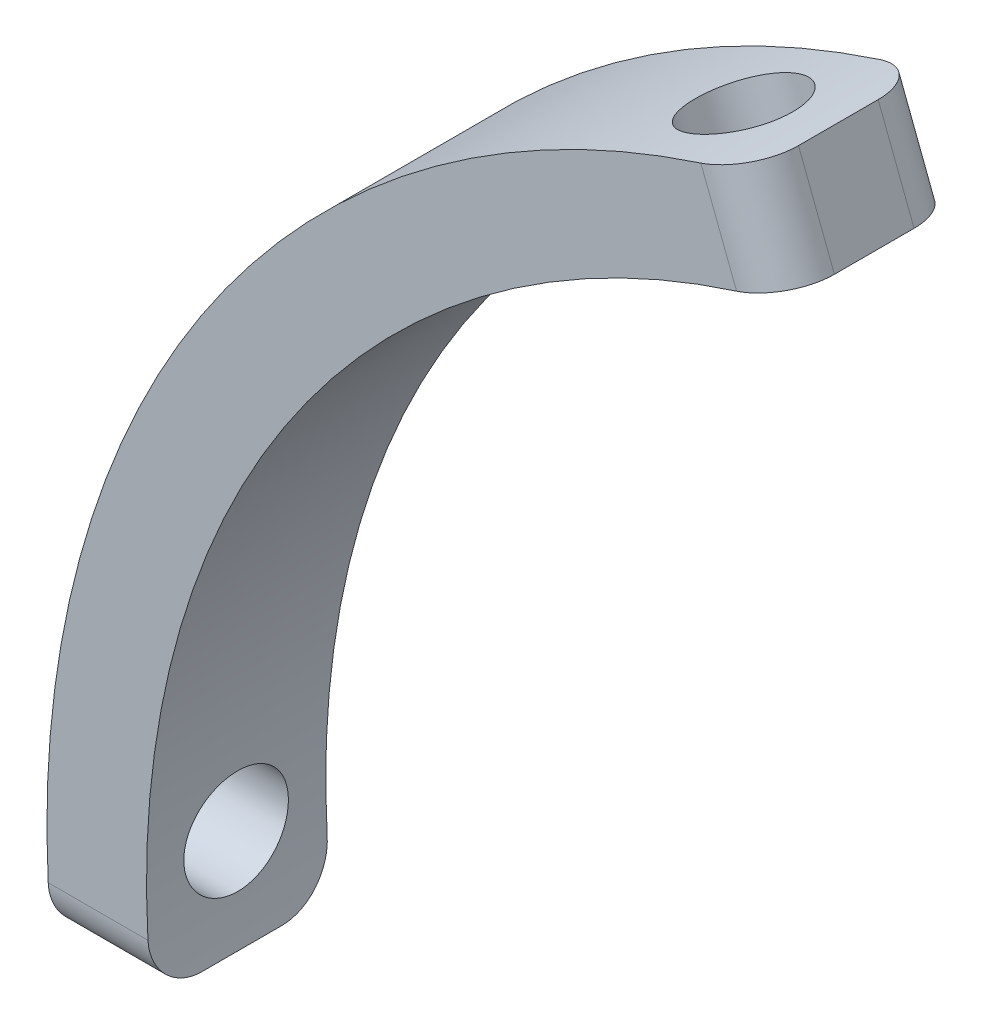
SolidWorks part; units mm, degrees
material "Plain Carbon Steel"
ref_plane "Front Plane" through (0, 0, 0) normal (0, 0, 1) x (1, 0, 0)
ref_plane "Top Plane" through (0, 0, 0) normal (0, 1, 0) x (1, 0, 0)
ref_plane "Right Plane" through (0, 0, 0) normal (1, 0, 0) x (0, 0, -1)
sketch "Sketch1" plane through (0, 0, 0) normal (0, 0, 1) x (1, 0, 0)
  line L0 (-90, 0) -> (0, 0) construction
  line L1 (0, 0) -> (-32.2531, 84.0222) construction
  line L4 (-7.275, 5) -> (-35.0764, 77.4251) construction
  line L5 (-84.8528, 5) -> (-7.275, 5) construction
  line L6 (-24.52, 91.7811) -> (-20.9139, 82.3869)
  line L7 (-94.4722, -10) -> (-84.4097, -10)
  arc A0 (-90, 0) -> (-32.2531, 84.0222) centre (0, 0) cw construction
  arc A1 (-84.4097, -10) -> (-20.9139, 82.3869) centre (0, 0) cw
  arc A6 (-84.8528, 5) -> (-35.0764, 77.4251) centre (0, 0) cw construction
  arc A7 (-94.4722, -10) -> (-24.52, 91.7811) centre (0, 0) cw
  arc A8 (-95, 0) -> (-34.045, 88.6901) centre (0, 0) cw construction
  dimension "D1" = 90
  dimension "D3" = 5
  dimension "D4" = 5
  dimension "D2" = 69
  dimension "D5" = 10
  dimension "D6" = 10
extrude "Boss-Extrude3" add sketch "Sketch1" along normal mid plane 18
ref_plane "Plane3" through (-34.045, 88.6901, 0) normal (-0.3584, 0.9336, 0) x (0.9336, 0.3584, 0)
sketch "Sketch5" plane through (-34.045, 88.6901, 0) normal (-0.3584, 0.9336, 0) x (0.9336, 0.3584, 0)
  circle A0 centre (0, 0) radius 5.25
  dimension "D1" = 10.5
extrude "Cut-Extrude4" cut sketch "Sketch5" against normal blind 18
ref_plane "Plane4" through (-95, 0, 0) normal (-1, 0, 0) x (0, 0, 1)
sketch "Sketch6" plane through (-95, 0, 0) normal (-1, 0, 0) x (0, 0, 1)
  circle A0 centre (0, 0) radius 5.25
  dimension "D1" = 10.5
extrude "Cut-Extrude5" cut sketch "Sketch6" against normal blind 18
fillet "Fillet1" radius 5 4 edges at (-89.441, -10, -9) (-89.441, -10, 9) (-22.717, 87.084, -9) (-22.717, 87.084, 9)
